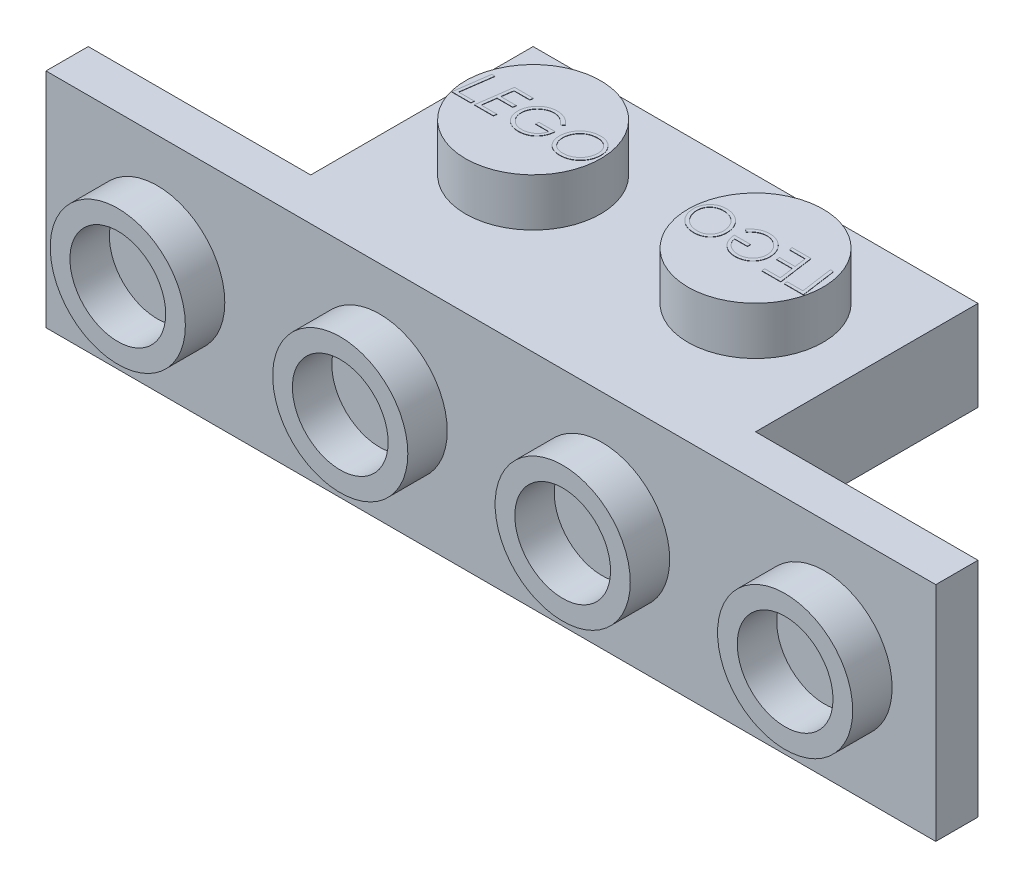
SolidWorks part; units mm, degrees
ref_plane "Front Plane" through (0, 0, 0) normal (0, 0, 1) x (1, 0, 0)
ref_plane "Top Plane" through (0, 0, 0) normal (0, 1, 0) x (1, 0, 0)
ref_plane "Right Plane" through (0, 0, 0) normal (1, 0, 0) x (0, 0, -1)
sketch "Sketch1" plane through (0, 0, 0) normal (0, 1, 0) x (1, 0, 0)
  line L0 (0, 0) -> (7.9, 0)
  line L1 (7.9, 0) -> (7.9, 7.9)
  line L2 (0, 0) -> (0, 7.9)
  line L3 (0, 7.9) -> (7.9, 7.9)
  dimension "D1" = 7.9
  dimension "D2" = 7.9
  dimension "D3" = 7.9
extrude "Boss-Extrude1" add sketch "Sketch1" along normal blind 3.2
sketch "Sketch2" plane through (0, 3.2, 0) normal (0, 1, 0) x (1, 0, 0)
  line L0 (0, 7.9) -> (7.9, 0) construction
  circle A0 centre (3.95, 3.95) radius 2.4
extrude "Boss-Extrude2" add sketch "Sketch2" along normal blind 1.7
sketch "Sketch3" plane through (0, 4.9, 0) normal (0, 1, 0) x (1, 0, 0)
  line L0 (1.625, 3.3549) -> (6.275, 3.3549) construction
  circle A0 centre (3.95, 3.95) radius 2.4 construction
  circle A1 centre (3.95, 3.95) radius 2.4 construction
  text T0 "<i>LEGO</i>" font "Century Gothic" height 1.25
extrude "Boss-Extrude4" add sketch "Sketch3" along normal blind 0.01
sketch "Sketch4" plane through (0, 0, 0) normal (0, -1, 0) x (1, 0, 0)
  line L0 (7.9, -7.9) -> (0, -7.9) construction
  line L1 (7.3, -7.3) -> (0.6204, -7.3)
  line L2 (7.3, -7.3) -> (7.3, -0.6204)
  line L3 (7.3, -0.6204) -> (0.6204, -0.6204)
  line L4 (0.6204, -7.3) -> (0.6204, -0.6204)
  line L5 (7.9, 0) -> (7.9, -7.9) construction
  dimension "D1" = 0.6
  dimension "D2" = 0.6
extrude "Cut-Extrude1" cut sketch "Sketch4" against normal blind 2.01 contours L2 L1 L4 L3
sketch "Sketch5" plane through (0, 3.2, 0) normal (0, 1, 0) x (1, 0, 0)
  line L1 (1.4581, 1.5578) -> (6.3695, 1.5578)
  line L2 (1.4581, 1.5578) -> (1.4581, 6.3652)
  line L3 (1.4581, 6.3652) -> (6.3695, 6.3652)
  line L4 (6.3695, 1.5578) -> (6.3695, 6.3652)
  circle A1 centre (6.3695, 6.3652) radius 1.0161
  circle A2 centre (6.3695, 1.5578) radius 1.0061
  circle A3 centre (1.4581, 1.5578) radius 1.0219
  circle A4 centre (1.4581, 6.3652) radius 1.0411
  circle M5 centre (3.95, 3.95) radius 2.4
extrude "Boss-Extrude5" add sketch "Sketch5" against normal blind 2.01 contours L1 A2 L4 | L2 A3 L1 | L1 A3 L2 | L4 A2 L1 M5 | L4 A1 L3 | L3 A1 L4 | L2 A4 L3 | L3 A4 L2
mirror "Mirror1" about plane through (7.9, 3.2, 0) normal (-1, 0, 0) of bodies 106
sketch "Sketch6" plane through (0, 0, 0) normal (0, 0, 1) x (1, 0, 0)
  line L0 (0, 3.2) -> (15.8, 3.2) construction
  line L1 (23.7, 3.2) -> (-7.9, 3.2)
  line L2 (7.9, 3.2) -> (7.9, -4.7)
  line L3 (23.7, -4.7) -> (-7.9, -4.7)
  line L4 (-7.9, 3.2) -> (-7.9, -4.7)
  line L5 (23.7, 3.2) -> (23.7, -4.7)
  line M6 (0, 0) -> (15.8, 0)
  line M7 (15.8, 0) -> (15.8, 3.2)
  line M8 (15.8, 3.2) -> (0, 3.2)
  line M9 (0, 3.2) -> (0, 0)
  dimension "D1" = 15.8
  dimension "D2" = 7.9
extrude "Boss-Extrude6" add sketch "Sketch6" along normal blind 1.5 contours L1 L4 L3 L2 M6 M9 | L2 L1 M9 M6 | L2 M8 M6 M7 | L5 L1 L2 L3 M7 M6
sketch "Sketch7" plane through (0, 0, 1.5) normal (0, 0, 1) x (1, 0, 0)
  line L0 (-7.9, 3.2) -> (0, -4.7) construction
  line L1 (23.7, -4.7) -> (-7.9, -4.7) construction
  line L2 (-7.9, -0.75) -> (23.7, -0.75) construction
  line L3 (-7.9, 3.2) -> (-7.9, -4.7) construction
  line L4 (23.7, 3.2) -> (23.7, -4.7) construction
  circle A0 centre (-3.95, -0.75) radius 2.4
  circle A1 centre (-3.95, -0.75) radius 1.7
  circle A2 centre (3.95, -0.75) radius 2.4
  circle A3 centre (3.95, -0.75) radius 1.7
  circle A4 centre (11.85, -0.75) radius 2.4
  circle A5 centre (11.85, -0.75) radius 1.7
  circle A6 centre (19.75, -0.75) radius 2.4
  circle A7 centre (19.75, -0.75) radius 1.7
  dimension "D1" = 4.8
  dimension "D2" = 3.4
extrude "Boss-Extrude7" add sketch "Sketch7" along normal blind 1.4
